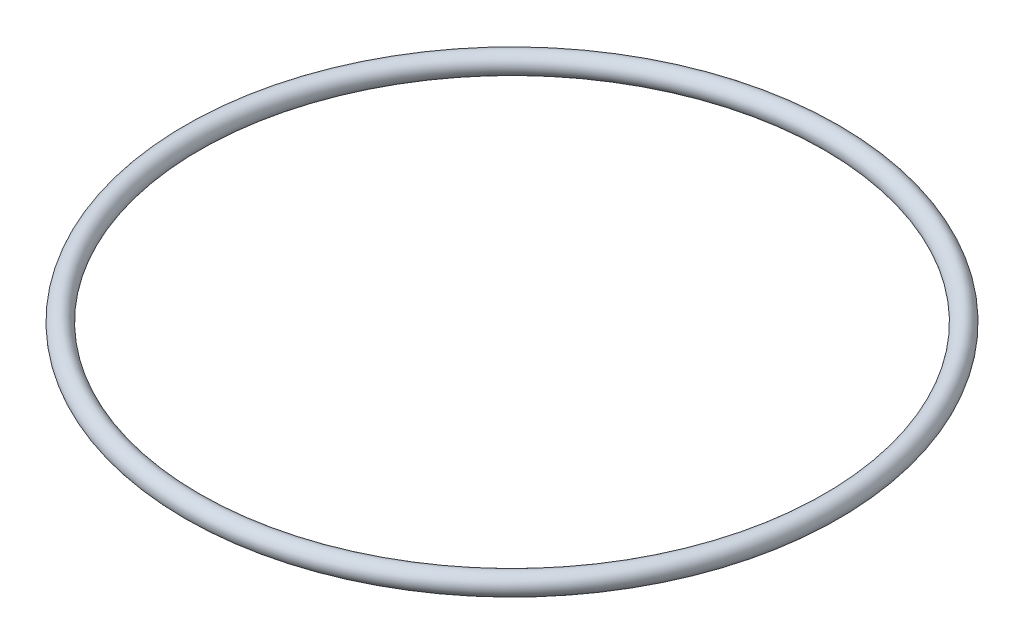
SolidWorks part; units mm, degrees
ref_plane "Front Plane" through (0, 0, 0) normal (0, 0, 1) x (1, 0, 0)
ref_plane "Top Plane" through (0, 0, 0) normal (0, 1, 0) x (1, 0, 0)
ref_plane "Right Plane" through (0, 0, 0) normal (1, 0, 0) x (0, 0, -1)
sketch "Sketch1" plane through (0, 0, 0) normal (0, 0, 1) x (1, 0, 0)
  line L0 (0, 19.797) -> (0, -19.5941) construction
  circle A0 centre (135.7, 0) radius 4.3
  dimension "D1" = 8.6
  dimension "D2" = 271.4
revolve "Revolve1" add sketch "Sketch1" angle 360 about L0
